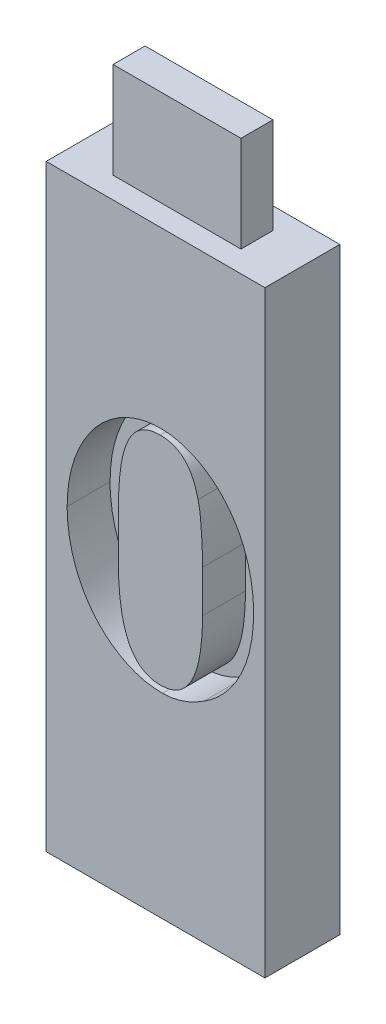
SolidWorks part; units mm, degrees
ref_plane "Front Plane" through (0, 0, 0) normal (0, 0, 1) x (1, 0, 0)
ref_plane "Top Plane" through (0, 0, 0) normal (0, 1, 0) x (1, 0, 0)
ref_plane "Right Plane" through (0, 0, 0) normal (1, 0, 0) x (0, 0, -1)
sketch "Sketch1" plane through (0, 0, 0) normal (0, 0, 1) x (1, 0, 0)
  line L1 (-8.69, -23.749) -> (8.69, -23.749)
  line L2 (-8.69, -23.749) -> (-8.69, 23.749)
  line L3 (-8.69, 23.749) -> (8.69, 23.749)
  line L4 (8.69, -23.749) -> (8.69, 23.749)
  line L5 (-8.69, -23.749) -> (8.69, 23.749) construction
  line L6 (-8.69, 23.749) -> (8.69, -23.749) construction
  point P0 (0, 0)
  dimension "D1" = 17.38
  dimension "D2" = 47.498
extrude "Boss-Extrude1" add sketch "Sketch1" along normal blind 5.95
sketch "Sketch2" plane through (0, 0, 5.95) normal (0, 0, 1) x (1, 0, 0)
  line L0 (0, 23.749) -> (0, -23.749) construction
  line L1 (8.69, 23.749) -> (-8.69, 23.749) construction
  line L2 (-8.69, -23.749) -> (8.69, -23.749) construction
  line L3 (0, -23.749) -> (0, 0) construction
  line L4 (0, 0) -> (-8.69, 0) construction
  line L5 (-8.69, 23.749) -> (-8.69, -23.749) construction
  line L6 (-8.69, 0) -> (8.69, 0) construction
  line L7 (8.69, -23.749) -> (8.69, 23.749) construction
  line L8 (-8.69, -23.749) -> (8.69, -23.749) construction
  line L9 (-8.69, -21.209) -> (8.69, -21.209) construction
  line L10 (-8.69, -18.669) -> (8.69, -18.669) construction
  line L11 (-8.69, -16.129) -> (8.69, -16.129) construction
  line L12 (-8.69, -13.589) -> (8.69, -13.589) construction
  line L13 (-8.69, -11.049) -> (8.69, -11.049) construction
  line L14 (-8.69, -8.509) -> (8.69, -8.509) construction
  line L15 (-8.69, -5.969) -> (8.69, -5.969) construction
  line L16 (-8.69, -3.429) -> (8.69, -3.429) construction
  line L17 (-8.69, -0.889) -> (8.69, -0.889) construction
  line L18 (-8.69, 1.651) -> (8.69, 1.651) construction
  line L19 (-8.69, 4.191) -> (8.69, 4.191) construction
  line L20 (-8.69, 6.731) -> (8.69, 6.731) construction
  line L21 (-8.69, 9.271) -> (8.69, 9.271) construction
  line L22 (-8.69, 11.811) -> (8.69, 11.811) construction
  line L23 (-8.69, 14.351) -> (8.69, 14.351) construction
  line L24 (-8.69, 16.891) -> (8.69, 16.891) construction
  line L25 (-8.69, 19.431) -> (8.69, 19.431) construction
  line L26 (-8.69, 21.971) -> (8.69, 21.971) construction
  line L27 (-8.69, 23.749) -> (-8.69, -23.749) construction
  line L28 (-6.15, 23.749) -> (-6.15, -23.749) construction
  line L29 (-3.61, 23.749) -> (-3.61, -23.749) construction
  line L30 (-1.07, 23.749) -> (-1.07, -23.749) construction
  line L31 (1.47, 23.749) -> (1.47, -23.749) construction
  line L32 (4.01, 23.749) -> (4.01, -23.749) construction
  line L33 (6.55, 23.749) -> (6.55, -23.749) construction
  text T0 "0\r\n" font "Engravers MT" height in points 72
  point P14 (0, 0)
  point P69 (-7.968, -5.969)
  point P70 (-8.2943, -5.969)
  point P71 (-8.0437, -5.969)
  point P72 (-7.9766, -7.9877)
  dimension "D1" = 19
  dimension "D2" = 2.54
  dimension "D4" = 2.54
  dimension "D3" = 7
extrude "Cut-Extrude1" cut sketch "Sketch2" against normal blind 3.41
sketch "Sketch3" plane through (0, 23.749, 0) normal (0, 1, 0) x (1, 0, 0)
  line L0 (0, 0) -> (0, -5.95) construction
  line L1 (8.69, -5.95) -> (-8.69, -5.95) construction
  line L2 (0, -5.95) -> (0, -2.975) construction
  line L3 (0, -2.975) -> (-8.69, -2.975) construction
  line L4 (-8.69, -5.95) -> (-8.69, 0) construction
  line L5 (-8.69, -2.975) -> (8.69, -2.975) construction
  line L6 (8.69, -5.95) -> (8.69, 0) construction
  line L8 (-5.08, -4.245) -> (5.08, -4.245)
  line L9 (-5.08, -4.245) -> (-5.08, -1.705)
  line L10 (-5.08, -1.705) -> (5.08, -1.705)
  line L11 (5.08, -4.245) -> (5.08, -1.705)
  line L12 (-5.08, -4.245) -> (5.08, -1.705) construction
  line L13 (-5.08, -1.705) -> (5.08, -4.245) construction
  dimension "D1" = 2.54
  dimension "D2" = 10.16
extrude "Boss-Extrude2" add sketch "Sketch3" along normal blind 7.62
